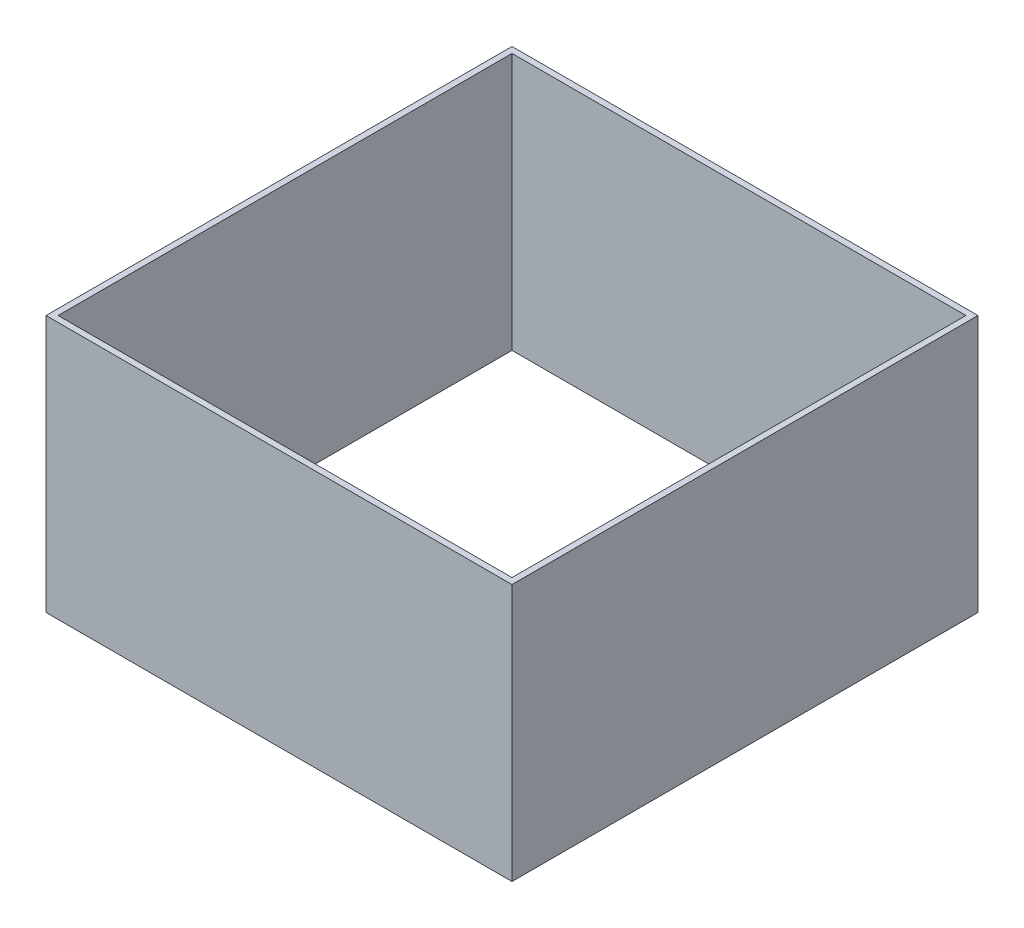
SolidWorks part; units mm, degrees
ref_plane "Front Plane" through (0, 0, 0) normal (0, 0, 1) x (1, 0, 0)
ref_plane "Top Plane" through (0, 0, 0) normal (0, 1, 0) x (1, 0, 0)
ref_plane "Right Plane" through (0, 0, 0) normal (1, 0, 0) x (0, 0, -1)
sketch "Sketch1" plane through (0, 0, 0) normal (0, 1, 0) x (1, 0, 0)
  line L0 (1, 1) -> (76, 1)
  line L1 (0, 0) -> (77, 0)
  line L2 (0, 0) -> (0, 77)
  line L3 (0, 77) -> (77, 77)
  line L4 (77, 0) -> (77, 77)
  line L9 (76, 1) -> (76, 76)
  line L10 (1, 76) -> (76, 76)
  line L11 (1, 1) -> (1, 76)
  dimension "D1" = 77
  dimension "D2" = 77
  dimension "D3" = 1
extrude "Boss-Extrude1" add sketch "Sketch1" along normal blind 42.5
